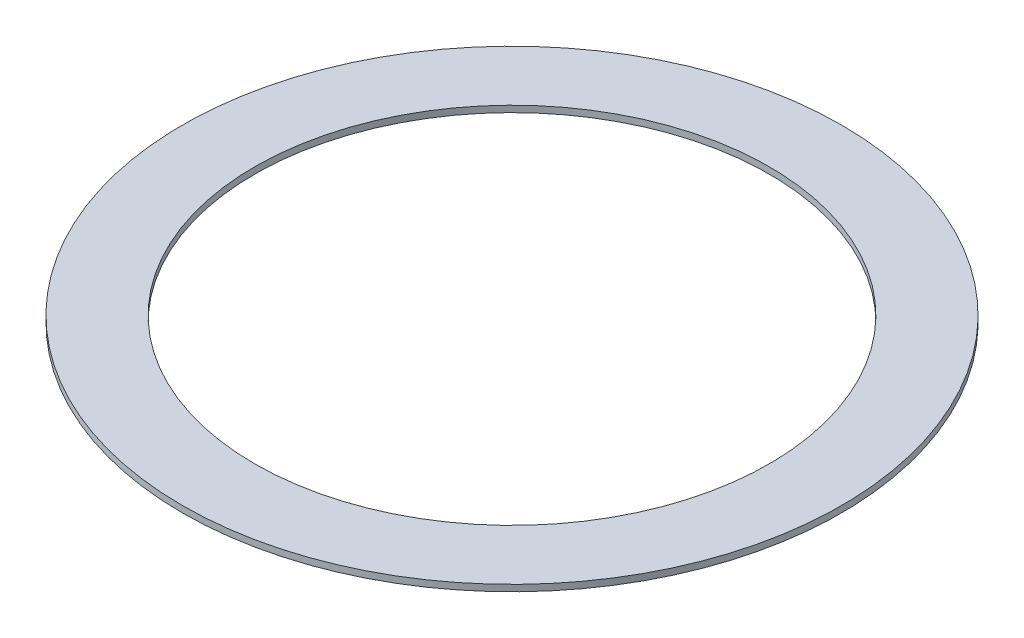
SolidWorks part; units mm, degrees
material "AISI 316 Stainless Steel Sheet (SS)"
ref_plane "Front Plane" through (0, 0, 0) normal (0, 0, 1) x (1, 0, 0)
ref_plane "Top Plane" through (0, 0, 0) normal (0, 1, 0) x (1, 0, 0)
ref_plane "Right Plane" through (0, 0, 0) normal (1, 0, 0) x (0, 0, -1)
sketch "Sketch1" plane through (0, 0, 0) normal (0, 1, 0) x (1, 0, 0)
  circle A0 centre (0, 0) radius 32.0294
  circle A1 centre (0, 0) radius 41.021
  dimension "D1" = 82.042
  dimension "D2" = 8.9916
extrude "Boss-Extrude1" add sketch "Sketch1" along normal mid plane 0.8001
